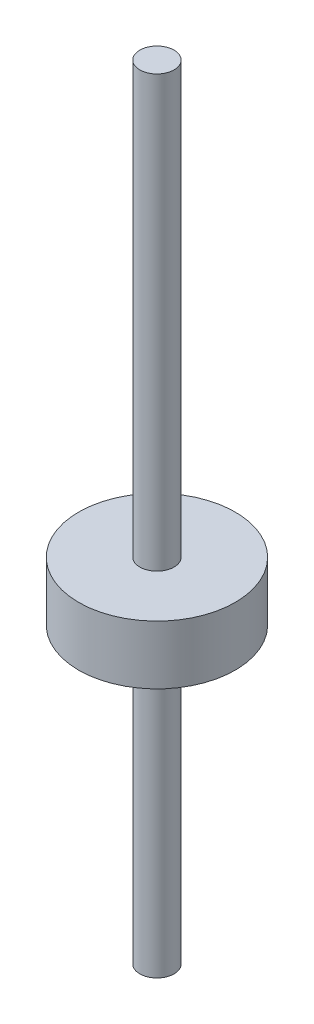
SolidWorks part; units mm, degrees
ref_plane "Front Plane" through (0, 0, 0) normal (0, 0, 1) x (1, 0, 0)
ref_plane "Top Plane" through (0, 0, 0) normal (0, 1, 0) x (1, 0, 0)
ref_plane "Right Plane" through (0, 0, 0) normal (1, 0, 0) x (0, 0, -1)
sketch "Sketch1" plane through (0, 0, 0) normal (0, 1, 0) x (1, 0, 0)
  circle A0 centre (0, 0) radius 0.875
  dimension "D1" = 1.75
extrude "Boss-Extrude2" add sketch "Sketch1" along normal blind 18 contours A0
sketch "Sketch3" plane through (0, 18, 0) normal (0, 1, 0) x (1, 0, 0)
  circle A0 centre (0, 0) radius 4
  dimension "D1" = 8
extrude "Boss-Extrude3" add sketch "Sketch3" against normal blind 3
sketch "Sketch4" plane through (0, 18, 0) normal (0, 1, 0) x (1, 0, 0)
  circle A0 centre (0, 0) radius 0.875
  dimension "D1" = 1.75
extrude "Boss-Extrude4" add sketch "Sketch4" along normal blind 22
